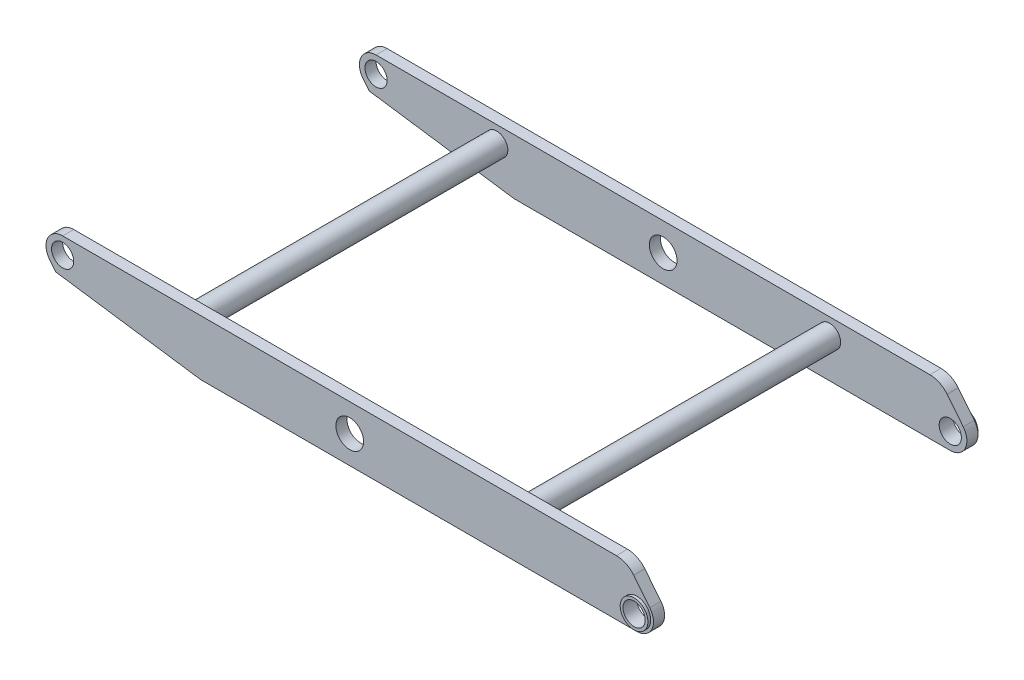
SolidWorks part; units mm, degrees
ref_plane "前基準面" through (0, 0, 0) normal (0, 0, 1) x (1, 0, 0)
ref_plane "上基準面" through (0, 0, 0) normal (0, 1, 0) x (1, 0, 0)
ref_plane "右基準面" through (0, 0, 0) normal (1, 0, 0) x (0, 0, -1)
sketch "草圖1" plane through (0, 0, 0) normal (0, 0, 1) x (1, 0, 0)
  line L4 (-48.0775, -5) -> (51.7581, -5)
  line L5 (54.1007, -0.1259) -> (51.201, 3.4988)
  line L6 (48.0775, 5) -> (-51.7581, 5)
  line L7 (-54.1007, 0.1259) -> (-51.201, -3.4988)
  line L8 (0, 0) -> (0, 24.3095) construction
  line L9 (-26.8908, -5) -> (-53.0026, -1.2468)
  arc A0 (51.7581, -5) -> (54.1007, -0.1259) centre (51.7581, -2) ccw
  arc A1 (-51.7581, 5) -> (-54.1007, 0.1259) centre (-51.7581, 2) ccw
  arc A2 (51.201, 3.4988) -> (48.0775, 5) centre (48.0775, 1) ccw
  arc A3 (-48.0775, -5) -> (-51.201, -3.4988) centre (-48.0775, -1) cw
  circle A4 centre (0, 0) radius 2.5
  point P9 (58, -5)
  point P12 (-58, 5)
  point P15 (50, 5)
  dimension "D6" = 3
  dimension "D7" = 4
  dimension "D8" = 5
  dimension "D1" = 58
  dimension "D2" = 50
  dimension "D3" = 58
  dimension "D4" = 10
  dimension "D5" = 5
extrude "填料-伸長1" add sketch "草圖1" along normal blind 2
sketch "草圖4" plane through (0, 0, 2) normal (0, 0, 1) x (1, 0, 0)
  circle A0 centre (51.7581, -2) radius 2.5
  arc A2 (51.7581, -5) -> (54.1007, -0.1259) centre (51.7581, -2) ccw construction
  dimension "D1" = 5
extrude "填料-伸長3" add sketch "草圖4" along normal blind 0.5
sketch "草圖2" plane through (0, 0, 2) normal (0, 0, 1) x (1, 0, 0)
  circle A0 centre (-51.7581, 2) radius 2
  circle A1 centre (51.7581, -2) radius 2
  dimension "D1" = 4
extrude "除料-伸長1" cut sketch "草圖2" against normal through all and the other way through all
sketch "草圖3" plane through (0, 0, 2) normal (0, 0, -1) x (-1, 0, 0)
  line L0 (0, 0) -> (0, 28.0589) construction
  circle A0 centre (30, 2) radius 2
  circle A1 centre (-30, 2) radius 2
  dimension "D1" = 2
  dimension "D2" = 4
  dimension "D3" = 30
extrude "填料-伸長2" add sketch "草圖3" along normal blind 29.25
mirror "鏡射1" about plane through (-30, 2, -27.25) normal (0, 0, -1) of bodies 103
